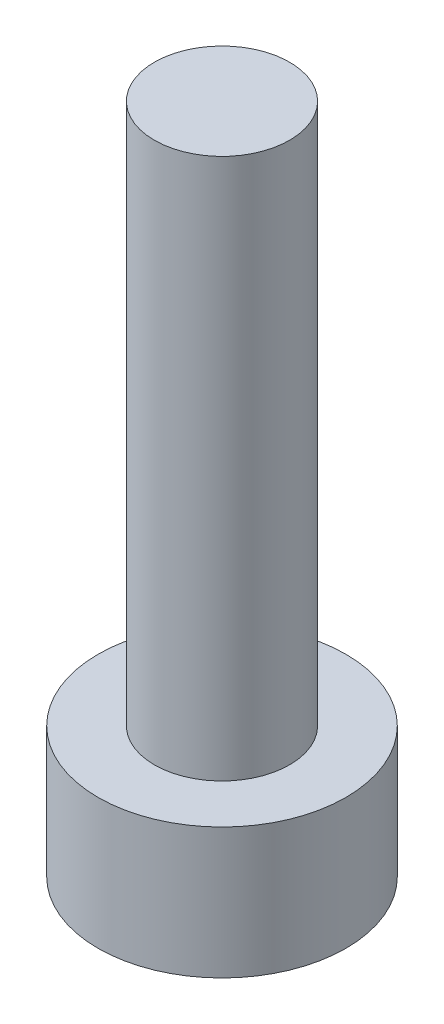
SolidWorks part; units mm, degrees
material "铸造碳钢"
ref_plane "前视基准面" through (0, 0, 0) normal (0, 0, 1) x (1, 0, 0)
ref_plane "上视基准面" through (0, 0, 0) normal (0, 1, 0) x (1, 0, 0)
ref_plane "右视基准面" through (0, 0, 0) normal (1, 0, 0) x (0, 0, -1)
other "Configuration Table"
sketch "草图1" plane through (0, 0, 0) normal (0, 1, 0) x (1, 0, 0)
  circle A0 centre (0, 0) radius 1.5
  dimension "D1" = 3
extrude "凸台-拉伸1" add sketch "草图1" along normal blind 12
sketch "草图2" plane through (0, 0, 0) normal (0, -1, 0) x (1, 0, 0)
  circle A0 centre (0, 0) radius 2.75
  dimension "D1" = 5.5
extrude "凸台-拉伸2" add sketch "草图2" along normal blind 2.9
sketch "草图3" plane through (0, -2.9, 0) normal (0, -1, 0) x (1, 0, 0)
  line L0 (0, 0) -> (0, 2.8092) construction
  line L1 (1.25, 0.7217) -> (0, 1.4434)
  line L2 (0, 1.4434) -> (-1.25, 0.7217)
  line L3 (-1.25, 0.7217) -> (-1.25, -0.7217)
  line L4 (-1.25, -0.7217) -> (0, -1.4434)
  line L5 (0, -1.4434) -> (1.25, -0.7217)
  line L6 (1.25, -0.7217) -> (1.25, 0.7217)
  circle A0 centre (0, 0) radius 1.25 construction
  dimension "D1" = 2.5
extrude "切除-拉伸1" cut sketch "草图3" against normal blind 1.5
